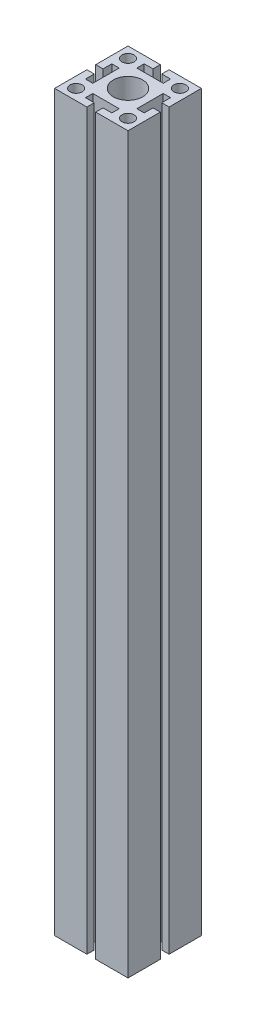
SolidWorks part; units mm, degrees
ref_plane "Front Plane" through (0, 0, 0) normal (0, 0, 1) x (1, 0, 0)
ref_plane "Top Plane" through (0, 0, 0) normal (0, 1, 0) x (1, 0, 0)
ref_plane "Right Plane" through (0, 0, 0) normal (1, 0, 0) x (0, 0, -1)
sketch "Sketch1" plane through (0, 0, 0) normal (0, 1, 0) x (1, 0, 0)
  line L1 (-25, -3) -> (-25, -25)
  line L6 (9, 20) -> (9, 15)
  line L7 (9, 20) -> (3, 20)
  line L8 (9, 15) -> (-9, 15)
  line L9 (3, 20) -> (3, 25)
  line L10 (-3, 25) -> (-25, 25)
  line L11 (-25, 25) -> (-25, 3)
  line L12 (-25, -25) -> (-3, -25)
  line L13 (25, -25) -> (25, -3)
  line L14 (3, 25) -> (25, 25)
  line L15 (-3, 20) -> (-3, 25)
  line L16 (-9, 20) -> (-9, 15)
  line L17 (3, -25) -> (25, -25)
  line L18 (25, 3) -> (25, 25)
  line L19 (-3, 20) -> (-9, 20)
  line L21 (-20, 9) -> (-15, 9)
  line L22 (-20, 9) -> (-20, 3)
  line L24 (-15, 9) -> (-15, -9)
  line L27 (-20, 3) -> (-25, 3)
  line L28 (20, -9) -> (15, -9)
  line L29 (20, -9) -> (20, -3)
  line L30 (15, -9) -> (15, 9)
  line L31 (20, -3) -> (25, -3)
  line L32 (20, 3) -> (25, 3)
  line L33 (-20, -3) -> (-25, -3)
  line L34 (20, 9) -> (15, 9)
  line L35 (20, 3) -> (20, 9)
  line L40 (-20, -9) -> (-15, -9)
  line L41 (-20, -3) -> (-20, -9)
  line L42 (-9, -20) -> (-9, -15)
  line L43 (-9, -20) -> (-3, -20)
  line L44 (-9, -15) -> (9, -15)
  line L45 (-3, -20) -> (-3, -25)
  line L46 (3, -20) -> (3, -25)
  line L47 (9, -20) -> (9, -15)
  line L48 (3, -20) -> (9, -20)
  circle A0 centre (0, 0) radius 10
  circle A1 centre (-17.6777, 17.6777) radius 4.1387
  circle A2 centre (17.6777, 17.6777) radius 4.1387
  circle A3 centre (17.6777, -17.6777) radius 4.1387
  circle A4 centre (-17.6777, -17.6777) radius 4.1387
  point P44 (0, 0)
  point P46 (0, 0)
  dimension "D1" = 4
extrude "Boss-Extrude1" add sketch "Sketch1" along normal blind 500
